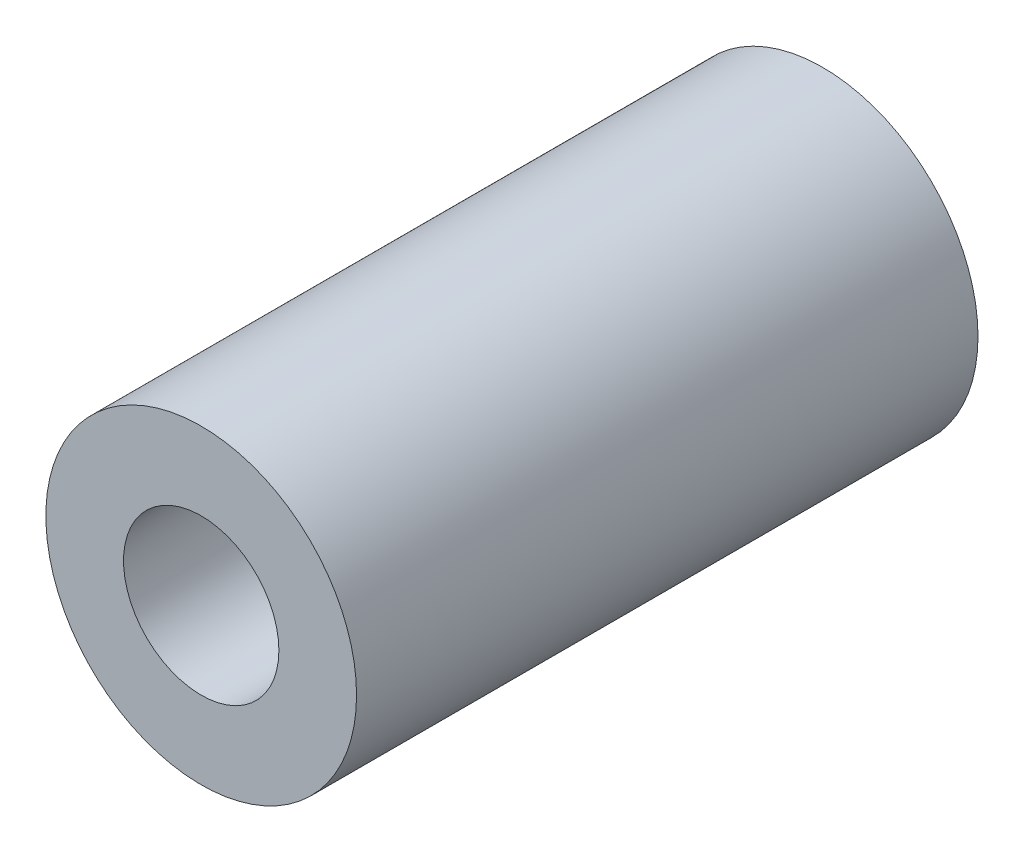
SolidWorks part; units mm, degrees
ref_plane "Front Plane" through (0, 0, 0) normal (0, 0, 1) x (1, 0, 0)
ref_plane "Top Plane" through (0, 0, 0) normal (0, 1, 0) x (1, 0, 0)
ref_plane "Right Plane" through (0, 0, 0) normal (1, 0, 0) x (0, 0, -1)
sketch "Sketch1" plane through (0, 0, 0) normal (0, 0, 1) x (1, 0, 0)
  circle A0 centre (0, 0) radius 3.175
  circle A1 centre (0, 0) radius 6.35
  dimension "D1" = 6.35
  dimension "D2" = 12.7
extrude "Boss-Extrude1" add sketch "Sketch1" along normal blind 25.4
